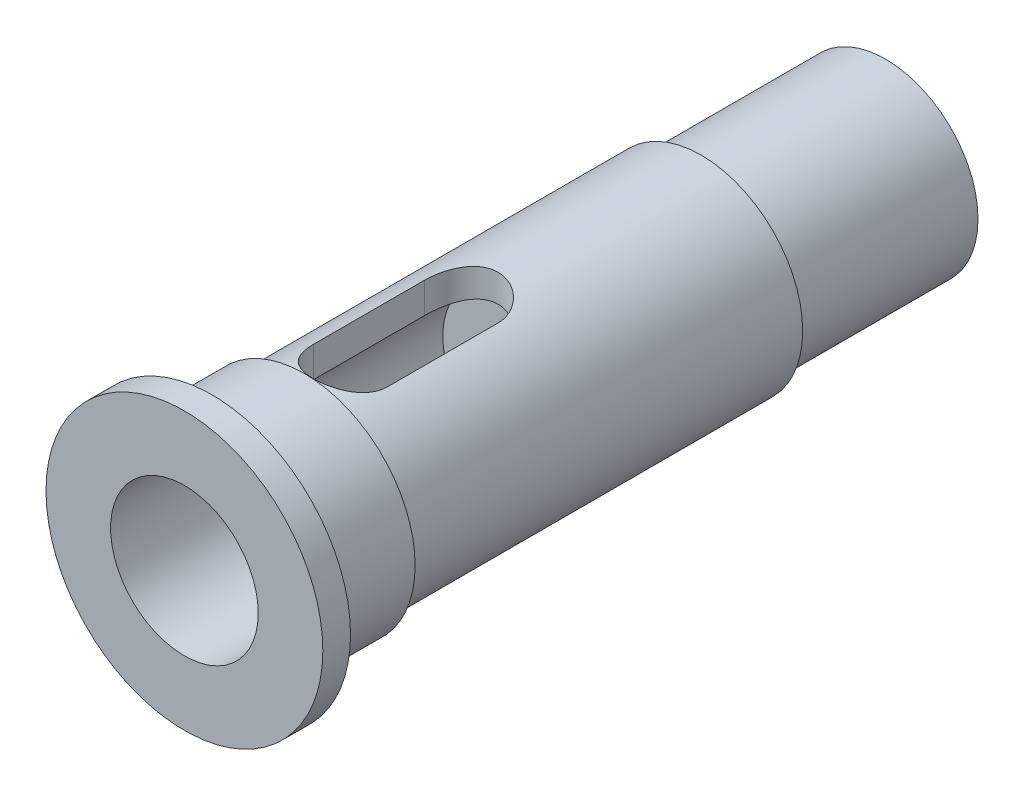
SolidWorks part; units mm, degrees
material "AISI 4130 Steel, annealed at 865C"
ref_plane "Front Plane" through (0, 0, 0) normal (0, 0, 1) x (1, 0, 0)
ref_plane "Top Plane" through (0, 0, 0) normal (0, 1, 0) x (1, 0, 0)
ref_plane "Right Plane" through (0, 0, 0) normal (1, 0, 0) x (0, 0, -1)
sketch "Sketch1" plane through (0, 0, 0) normal (0, 0, 1) x (1, 0, 0)
  circle A0 centre (0, 0) radius 5.5
  dimension "D1" = 11
extrude "Boss-Extrude1" add sketch "Sketch1" along normal blind 38
sketch "Sketch8" plane through (0, 0, 38) normal (0, 0, 1) x (1, 0, 0)
  circle A0 centre (0, 0) radius 7.5
  circle A1 centre (0, 0) radius 5.5 construction
  dimension "D1" = 15
extrude "Boss-Extrude2" add sketch "Sketch8" against normal blind 1.5
sketch "Sketch9" plane through (0, 0, 36.5) normal (0, 0, -1) x (-1, 0, 0)
  circle A0 centre (0, 0) radius 6
  dimension "D1" = 12
extrude "Boss-Extrude3" add sketch "Sketch9" along normal blind 5
sketch "Sketch2" plane through (0, 0, 38) normal (0, 0, 1) x (1, 0, 0)
  circle A0 centre (0, 0) radius 4
  dimension "D1" = 8
extrude "Cut-Extrude1" cut sketch "Sketch2" against normal blind 18
hole_wizard "M4x0.7 Tapped Hole1" [suppressed] positions "Sketch4" profile "Sketch6" tap size "M4x0.7" standard "ANSI Metric"
sketch "Sketch4" plane through (0, 0, 0) normal (0, 1, 0) x (1, 0, 0)
  line L0 (0, 0) -> (0, -23.314) construction
  line L2 (6, 0) -> (-6, 0) construction
  point P0 (0, -3.5)
  point P2 (0, -8.5)
  dimension "D1" = 3.5
  dimension "D2" = 5
sketch "Sketch6" plane through (0, 0, 3.5) normal (1, 0, 0) x (0, 0, -1)
  line L0 (0, 0) -> (0, 6)
  line L1 (0, 6) -> (1.65, 6)
  line L2 (1.65, 6) -> (1.65, 0)
  line L5 (1.65, 0) -> (0, 0)
  line L11 (0, -6.35) -> (0, 107.95) construction
  dimension "Thru Tap Drill Dia." = 3.3
  dimension "Thru Tap Drill Depth" = 6
cosmetic thread "Hole Thread1" [suppressed] parameters "D2"=4
cosmetic thread "Hole Thread2" [suppressed] parameters "D2"=4
ref_plane "Keyway slot plane" through (0, 5.5, 0) normal (0, 1, 0) x (1, 0, 0)
sketch "Sketch7" plane through (0, 5.5, 0) normal (0, 1, 0) x (1, 0, 0)
  line L0 (0, -29) -> (0, -23) construction
  line L1 (-2, -29) -> (-2, -23)
  line L2 (2, -29) -> (2, -23)
  line L4 (-4, -20) -> (4, -20) construction
  arc A0 (-2, -29) -> (2, -29) centre (0, -29) ccw
  arc A1 (2, -23) -> (-2, -23) centre (0, -23) ccw
  point P2 (0, -26)
  dimension "D2" = 10
  dimension "D1" = 4
  dimension "D3" = 1
extrude "Keyway slot" cut sketch "Sketch7" against normal blind 2.5
ref_plane "Plane2" through (0, 3, 0) normal (0, 1, 0) x (1, 0, 0)
ref_plane "Midkey plane" through (0, 0, 0) normal (-1, 0, 0) x (0, 0, 1)
sketch "Sketch11" plane through (0, 0, 0) normal (0, 0, -1) x (-1, 0, 0)
  circle A0 centre (0, 0) radius 5
  dimension "D1" = 10
extrude "Trim for M10 wheel nut" cut sketch "Sketch11" against normal blind 10 flip side to cut
cosmetic thread "Cosmetic Thread1" parameters "D2"=9
